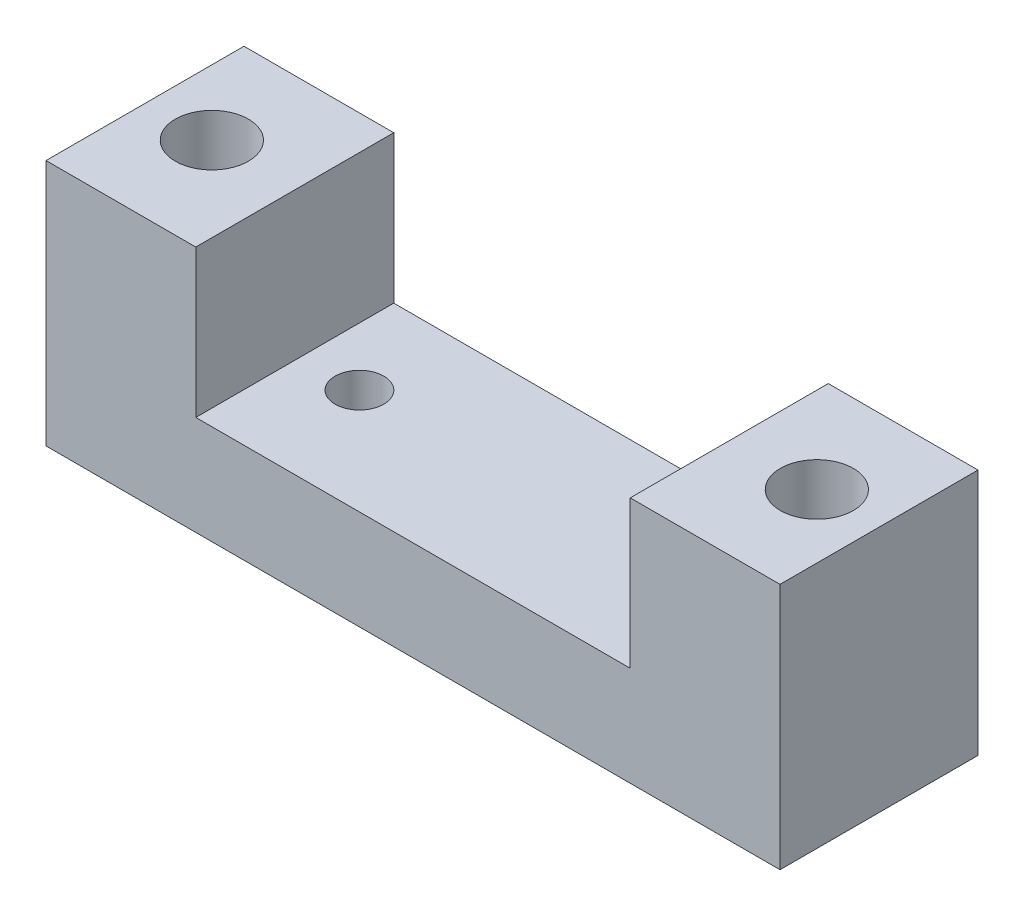
SolidWorks part; units mm, degrees
ref_plane "Front Plane" through (0, 0, 0) normal (0, 0, 1) x (1, 0, 0)
ref_plane "Top Plane" through (0, 0, 0) normal (0, 1, 0) x (1, 0, 0)
ref_plane "Right Plane" through (0, 0, 0) normal (1, 0, 0) x (0, 0, -1)
sketch "Sketch1" plane through (0, 0, 0) normal (0, 0, 1) x (1, 0, 0)
  line L0 (-15.07, 0) -> (-15.07, 10.15)
  line L1 (-15.07, 10.15) -> (-8.92, 10.15)
  line L2 (-8.92, 10.15) -> (-8.92, 4.09)
  line L3 (-8.92, 4.09) -> (8.92, 4.09)
  line L4 (8.92, 4.09) -> (8.92, 10.15)
  line L5 (8.92, 10.15) -> (15.07, 10.15)
  line L6 (15.07, 10.15) -> (15.07, 0)
  line L7 (15.07, 0) -> (-15.07, 0)
  point P4 (0, 4.09)
  point P10 (0, 0)
  point P12 (5.5807, 3.6574)
  point P13 (-15.07, 4.0057)
  point P14 (-6.1131, 1.9158)
  dimension "D1" = 30.14
  dimension "D2" = 10.15
  dimension "D3" = 4.09
  dimension "D4" = 6.15
extrude "Boss-Extrude1" add sketch "Sketch1" along normal blind 8.13
hole_wizard "Ø3.0mm Dowel Hole1" positions "Sketch2" profile "Sketch3" hole size "Ø3.0" standard "ISO"
sketch "Sketch2" plane through (0, 10.15, 0) normal (0, 1, 0) x (1, 0, 0)
  line L0 (-15.07, -8.13) -> (-15.07, 0) construction
  line L1 (15.07, -8.13) -> (15.07, 0) construction
  line L2 (-8.92, 0) -> (-15.07, 0) construction
  line L3 (15.07, 0) -> (8.92, 0) construction
  point P0 (-12.39, -4)
  point P2 (12.452, -4)
  dimension "D1" = 2.68
  dimension "D2" = 2.618
  dimension "D3" = 4
  dimension "D4" = 4
sketch "Sketch3" plane through (-12.39, 10.15, 4) normal (1, 0, 0) x (0, 0, 1)
  line L0 (0, 0) -> (0, 35.9013)
  line L1 (0, 35.9013) -> (1.5, 35)
  line L2 (1.5, 35) -> (1.5, 0)
  line L5 (1.5, 0) -> (0, 0)
  line L10 (0, 35.9013) -> (-1.5, 35) construction
  line L11 (0, -6.35) -> (0, 107.95) construction
  dimension "Hole Dia." = 3
  dimension "Hole Depth" = 35
  dimension "Drill Angle" = 118
hole_wizard "Ø2.0mm Dowel Hole1" positions "Sketch4" profile "Sketch5" hole size "Ø2.0" standard "ISO"
sketch "Sketch4" plane through (0, 4.09, 0) normal (0, 1, 0) x (1, 0, 0)
  line L0 (8.92, 0) -> (-8.92, 0) construction
  line L1 (15.07, -8.13) -> (15.07, 0) construction
  line L2 (-15.07, -8.13) -> (-15.07, 0) construction
  point P0 (-6.53, -3.8)
  point P2 (6.53, -3.8)
  dimension "D1" = 3.8
  dimension "D2" = 3.8
  dimension "D3" = 8.54
  dimension "D4" = 8.54
sketch "Sketch5" plane through (-6.53, 4.09, 3.8) normal (1, 0, 0) x (0, 0, 1)
  line L0 (0, 0) -> (0, 35.6009)
  line L1 (0, 35.6009) -> (1, 35)
  line L2 (1, 35) -> (1, 0)
  line L5 (1, 0) -> (0, 0)
  line L10 (0, 35.6009) -> (-1, 35) construction
  line L11 (0, -6.35) -> (0, 107.95) construction
  dimension "Hole Dia." = 2
  dimension "Hole Depth" = 35
  dimension "Drill Angle" = 118
